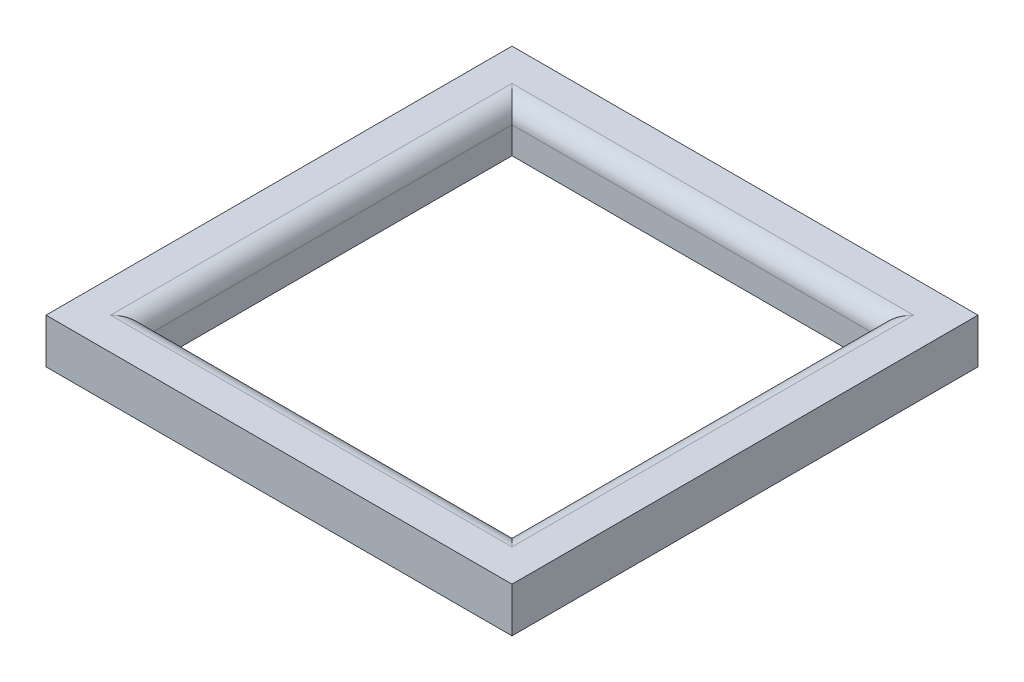
SolidWorks part; units mm, degrees
ref_plane "Front Plane" through (0, 0, 0) normal (0, 0, 1) x (1, 0, 0)
ref_plane "Top Plane" through (0, 0, 0) normal (0, 1, 0) x (1, 0, 0)
ref_plane "Right Plane" through (0, 0, 0) normal (1, 0, 0) x (0, 0, -1)
sketch "Sketch1" plane through (0, 0, 0) normal (0, 1, 0) x (1, 0, 0)
  line L1 (-10.2, 10.2) -> (10.2, 10.2)
  line L2 (-10.2, 10.2) -> (-10.2, -10.2)
  line L3 (-10.2, -10.2) -> (10.2, -10.2)
  line L4 (10.2, 10.2) -> (10.2, -10.2)
  line L5 (-10.2, 10.2) -> (10.2, -10.2) construction
  line L6 (-10.2, -10.2) -> (10.2, 10.2) construction
  line L7 (-13, 13) -> (13, 13)
  line L8 (-13, 13) -> (-13, -13)
  line L9 (-13, -13) -> (13, -13)
  line L10 (13, 13) -> (13, -13)
  line L11 (-13, 13) -> (13, -13) construction
  line L12 (-13, -13) -> (13, 13) construction
  point P0 (0, 0)
  point P6 (0, 0)
  dimension "D1" = 20.4
  dimension "D2" = 20.4
  dimension "D3" = 26
  dimension "D4" = 26
extrude "Boss-Extrude1" add sketch "Sketch1" along normal blind 2.5
fillet "Fillet1" radius 1 4 edges at (0, 2.5, 10.2) (10.2, 2.5, 0) (0, 2.5, -10.2) (-10.2, 2.5, 0)
